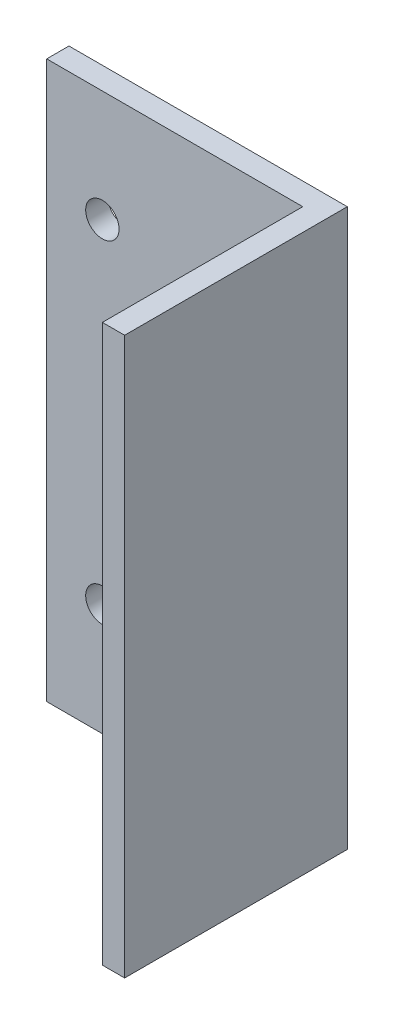
SolidWorks part; units mm, degrees
ref_plane "Front Plane" through (0, 0, 0) normal (0, 0, 1) x (1, 0, 0)
ref_plane "Top Plane" through (0, 0, 0) normal (0, 1, 0) x (1, 0, 0)
ref_plane "Right Plane" through (0, 0, 0) normal (1, 0, 0) x (0, 0, -1)
sketch "Sketch1" plane through (0, 0, 0) normal (0, 1, 0) x (1, 0, 0)
  line L0 (0, 0) -> (25, 0)
  line L1 (25, 0) -> (25, -20)
  line L2 (25, -20) -> (23, -20)
  line L3 (23, -20) -> (23, -2)
  line L4 (23, -2) -> (0, -2)
  line L5 (0, -2) -> (0, 0)
  dimension "D1" = 25
  dimension "D2" = 2
  dimension "D3" = 2
  dimension "D4" = 20
extrude "Boss-Extrude1" add sketch "Sketch1" along normal blind 50
sketch "Sketch2" plane through (0, 0, 0) normal (0, 0, -1) x (-1, 0, 0)
  line L0 (-25, 25) -> (0, 25) construction
  line L1 (-25, 50) -> (-25, 0) construction
  line L2 (0, 50) -> (0, 0) construction
  circle A0 centre (-5, 40) radius 1.5
  circle A1 centre (-5, 10) radius 1.5
  dimension "D1" = 3
  dimension "D2" = 5
  dimension "D3" = 30
extrude "Cut-Extrude1" cut sketch "Sketch2" against normal through all
